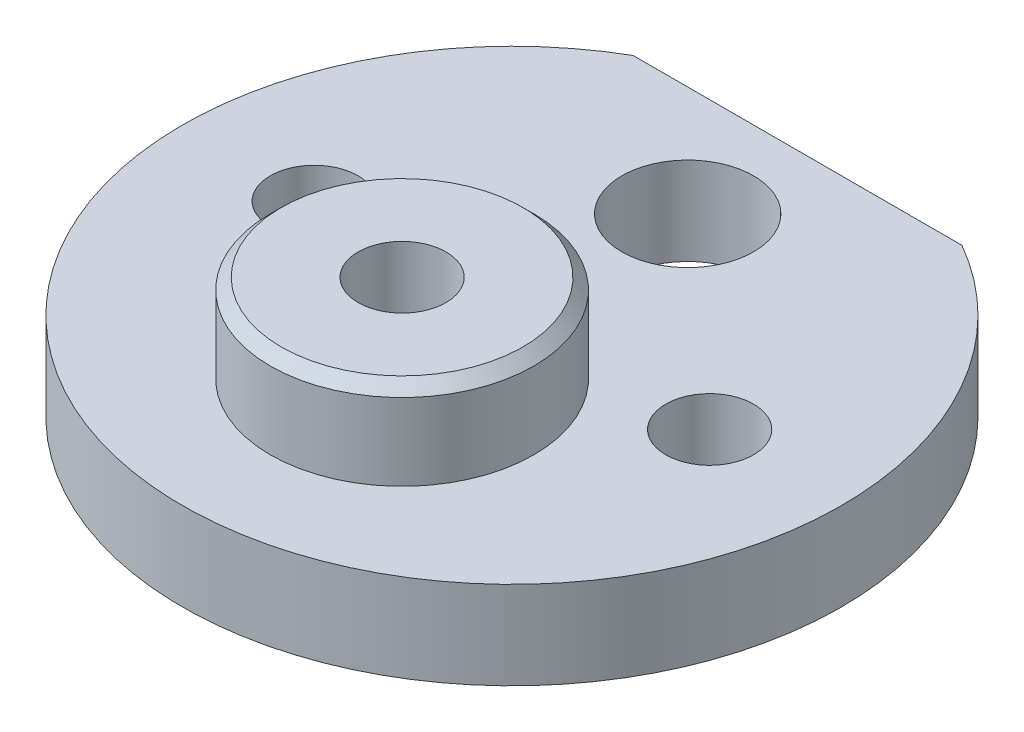
SolidWorks part; units mm, degrees
material "Alloy Steel"
ref_plane "Front Plane" through (0, 0, 0) normal (0, 0, 1) x (1, 0, 0)
ref_plane "Top Plane" through (0, 0, 0) normal (0, 1, 0) x (1, 0, 0)
ref_plane "Right Plane" through (0, 0, 0) normal (1, 0, 0) x (0, 0, -1)
sketch "Sketch1" plane through (0, 0, 0) normal (0, 1, 0) x (1, 0, 0)
  line L0 (-7.4833, 13) -> (7.4833, 13)
  arc A0 (-7.4833, 13) -> (7.4833, 13) centre (0, 0) ccw
  dimension "D1" = 30
  dimension "D2" = 13
extrude "Boss-Extrude1" add sketch "Sketch1" along normal blind 4
sketch "Sketch2" plane through (0, 4, 0) normal (0, 1, 0) x (1, 0, 0)
  circle A0 centre (0, 8) radius 3
  circle A1 centre (-9, 0) radius 2
  circle A2 centre (9, 0) radius 2
  dimension "D1" = 4
  dimension "D2" = 6
  dimension "D3" = 9
  dimension "D4" = 9
  dimension "D5" = 8
extrude "Cut-Extrude1" cut sketch "Sketch2" against normal through all
sketch "Sketch3" plane through (0, 4, 0) normal (0, 1, 0) x (1, 0, 0)
  circle A0 centre (0, -5) radius 6
  dimension "D1" = 12
  dimension "D2" = 5
extrude "Boss-Extrude2" add sketch "Sketch3" along normal blind 4
sketch "Sketch4" plane through (0, 8, 0) normal (0, 1, 0) x (1, 0, 0)
  circle A0 centre (0, -5) radius 2
  dimension "D1" = 4
extrude "Cut-Extrude2" cut sketch "Sketch4" against normal through all
chamfer "Chamfer1" distance 0.5 angle 45 1 edges at (0, 8, 11)
